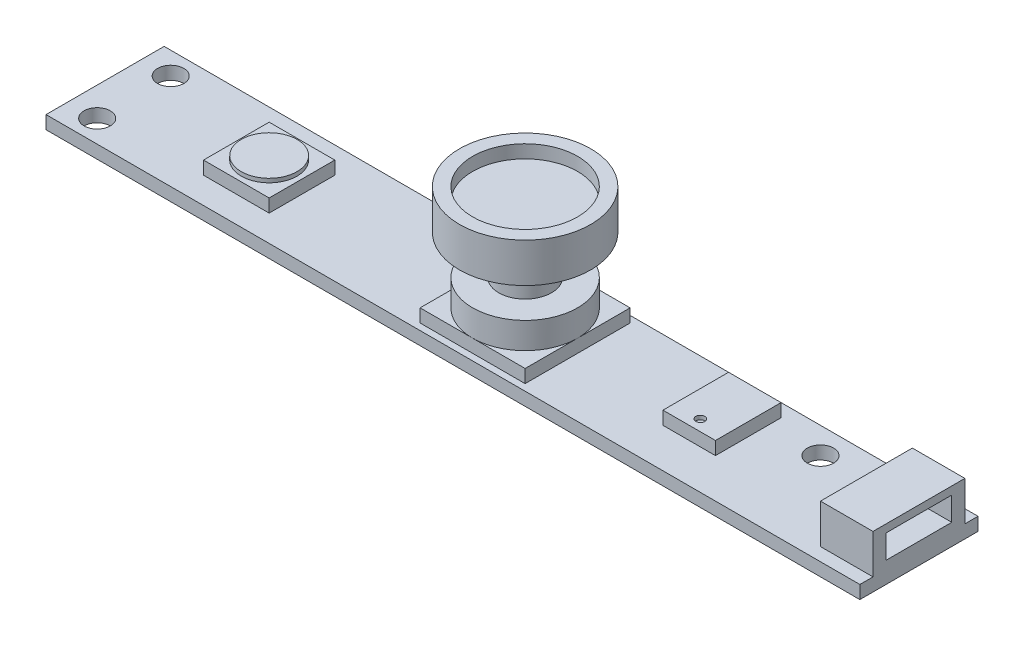
SolidWorks part; units mm, degrees
ref_plane "Front Plane" through (0, 0, 0) normal (0, 0, 1) x (1, 0, 0)
ref_plane "Top Plane" through (0, 0, 0) normal (0, 1, 0) x (1, 0, 0)
ref_plane "Right Plane" through (0, 0, 0) normal (1, 0, 0) x (0, 0, -1)
sketch "Sketch1" plane through (0, 0, 0) normal (0, 1, 0) x (1, 0, 0)
  line L1 (0, 0) -> (62, 0)
  line L2 (0, 0) -> (0, 9)
  line L3 (0, 9) -> (62, 9)
  line L4 (62, 0) -> (62, 9)
  dimension "D1" = 9
  dimension "D2" = 62
extrude "Boss-Extrude1" add sketch "Sketch1" along normal blind 1
sketch "Sketch2" plane through (0, 1, 0) normal (0, 1, 0) x (1, 0, 0)
  line L0 (62, 4.5) -> (0, 4.5) construction
  line L1 (62, 0) -> (62, 9) construction
  line L2 (0, 9) -> (0, 0) construction
  line L3 (31, 9) -> (31, 0) construction
  line L4 (62, 9) -> (0, 9) construction
  line L5 (0, 0) -> (62, 0) construction
  line L6 (62, 4.5) -> (62, 8)
  line L7 (62, 4.5) -> (62, 1)
  line L8 (62, 8) -> (58, 8)
  line L9 (58, 8) -> (58, 1)
  line L10 (58, 1) -> (62, 1)
  dimension "D1" = 3.5
  dimension "D2" = 3.5
  dimension "D3" = 4
extrude "Boss-Extrude2" add sketch "Sketch2" along normal blind 3
sketch "Sketch3" plane through (62, 0, 0) normal (1, 0, 0) x (0, 0, -1)
  line L11 (2, 3.4) -> (7, 3.4)
  line L12 (2, 3.4) -> (2, 1.6)
  line L13 (2, 1.6) -> (7, 1.6)
  line L14 (7, 3.4) -> (7, 1.6)
extrude "Cut-Extrude1" cut sketch "Sketch3" against normal blind 3
sketch "Sketch4" plane through (0, 1, 0) normal (0, 1, 0) x (1, 0, 0)
  line L0 (0, 4.5) -> (62, 4.5) construction
  line L1 (0, 9) -> (0, 0) construction
  line L2 (62, 1) -> (62, 8) construction
  line L4 (62, 9) -> (0, 9) construction
  line L5 (2.2, 9) -> (2.2, 0) construction
  line L6 (0, 0) -> (62, 0) construction
  circle A0 centre (2.2, 7.3) radius 1
  circle A1 centre (2.2, 1.7) radius 1
  circle A2 centre (52, 7) radius 1
extrude "Cut-Extrude2" cut sketch "Sketch4" against normal through all
sketch "Sketch5" plane through (0, 1, 0) normal (0, 1, 0) x (1, 0, 0)
  line L0 (62, 9) -> (62, 8)
  line L1 (62, 1) -> (62, 8) construction
  line L2 (62, 8) -> (31.4894, 8) construction
  line L3 (62, 9) -> (48, 9)
  line L4 (62, 9) -> (0, 9) construction
  line L5 (48, 9) -> (48, 0) construction
  line L6 (0, 0) -> (62, 0) construction
  line L8 (44, 9) -> (44, 0) construction
  line L9 (48, 8) -> (44, 8)
  line L10 (62, 3) -> (38.3098, 3) construction
  line L11 (48, 8) -> (48, 3)
  line L12 (48, 3) -> (44, 3)
  line L13 (44, 8) -> (44, 3)
  dimension "D1" = 1
  dimension "D2" = 14
extrude "Boss-Extrude4" add sketch "Sketch5" along normal blind 1 contours L9 L13 L12 L11
sketch "Sketch6" plane through (0, 1, 0) normal (0, 1, 0) x (1, 0, 0)
  line L0 (0, 9) -> (10, 9)
  line L1 (62, 9) -> (0, 9) construction
  line L2 (10, 9) -> (10, 0) construction
  line L3 (0, 0) -> (62, 0) construction
  line L4 (0, 4.5) -> (24.0117, 4.5) construction
  line L5 (0, 9) -> (0, 0) construction
  line L6 (10, 4.5) -> (10, 7)
  line L7 (10, 7) -> (15, 7)
  line L8 (15, 7) -> (15, 4.5)
  line L9 (15, 4.5) -> (15, 2)
  line L10 (15, 2) -> (10, 2)
  line L11 (10, 2) -> (10, 4.5)
  dimension "D1" = 10
  dimension "D2" = 2.5
  dimension "D3" = 2.5
  dimension "D4" = 5
extrude "Boss-Extrude5" add sketch "Sketch6" along normal blind 1 contours L11 L10 L9 L8 L7 L6
sketch "Sketch7" plane through (0, 2, 0) normal (0, 1, 0) x (1, 0, 0)
  line L0 (12.5, 7) -> (12.5, 2) construction
  line L1 (10, 7) -> (15, 7) construction
  line L2 (15, 2) -> (10, 2) construction
  line L3 (10, 4.5) -> (15, 4.5) construction
  line L4 (10, 2) -> (10, 7) construction
  line L5 (15, 7) -> (15, 2) construction
  circle A0 centre (12.5, 4.5) radius 2.126
extrude "Boss-Extrude6" add sketch "Sketch7" along normal blind 0.3
sketch "Sketch8" plane through (0, 1, 0) normal (0, 1, 0) x (1, 0, 0)
  line L0 (0, 4.5) -> (62, 4.5) construction
  line L1 (0, 9) -> (0, 0) construction
  line L2 (62, 1) -> (62, 8) construction
  line L3 (62, 9) -> (36, 9)
  line L4 (62, 9) -> (0, 9) construction
  line L5 (36, 9) -> (36, 0) construction
  line L6 (0, 0) -> (62, 0) construction
  line L7 (36, 9) -> (28, 9)
  line L8 (28, 9) -> (28, 0) construction
  line L9 (28, 4.5) -> (28, 0.5)
  line L10 (28, 0.5) -> (36, 0.5)
  line L11 (36, 0.5) -> (36, 4.5)
  line L12 (36, 4.5) -> (36, 8.5)
  line L13 (36, 8.5) -> (28, 8.5)
  line L14 (28, 8.5) -> (28, 4.5)
  dimension "D1" = 26
  dimension "D2" = 8
  dimension "D3" = 4
  dimension "D4" = 4
extrude "Boss-Extrude7" add sketch "Sketch8" along normal blind 1 contours L13 L14 L9 L10 L11 L12
sketch "Sketch9" plane through (0, 2, 0) normal (0, 1, 0) x (1, 0, 0)
  line L0 (28, 4.5) -> (36, 4.5) construction
  line L1 (28, 8.5) -> (28, 0.5) construction
  line L2 (36, 0.5) -> (36, 8.5) construction
  line L3 (32, 8.5) -> (32, 0.5) construction
  line L4 (36, 8.5) -> (28, 8.5) construction
  line L5 (28, 0.5) -> (36, 0.5) construction
  circle A0 centre (32, 4.5) radius 4
extrude "Boss-Extrude8" add sketch "Sketch9" along normal blind 2
sketch "Sketch10" plane through (0, 4, 0) normal (0, 1, 0) x (1, 0, 0)
  line L0 (32, 8.5) -> (32, 0.5) construction
  line L1 (28, 4.5) -> (36, 4.5) construction
  circle A0 centre (32, 4.5) radius 4 construction
  circle A1 centre (32, 4.5) radius 2.0145
extrude "Boss-Extrude9" add sketch "Sketch10" along normal blind 3
sketch "Sketch11" plane through (0, 7, 0) normal (0, 1, 0) x (1, 0, 0)
  line L0 (29.9855, 4.5) -> (34.0145, 4.5) construction
  line L1 (32, 6.5145) -> (32, 2.4855) construction
  circle A0 centre (32, 4.5) radius 2.0145 construction
  circle A1 centre (32, 4.5) radius 2.0145 construction
  circle A2 centre (32, 4.5) radius 5
extrude "Boss-Extrude10" add sketch "Sketch11" along normal blind 3
sketch "Sketch12" plane through (0, 10, 0) normal (0, 1, 0) x (1, 0, 0)
  line L0 (32, 9.5) -> (32, -0.5) construction
  circle A0 centre (32, 4.5) radius 5 construction
  circle A1 centre (32, 4.5) radius 4
extrude "Cut-Extrude3" cut sketch "Sketch12" against normal blind 1
sketch "Sketch13" plane through (0, 2, 0) normal (0, 1, 0) x (1, 0, 0)
  line L0 (46, 8) -> (46, 3) construction
  line L1 (48, 8) -> (44, 8) construction
  line L2 (48, 3) -> (44, 3) construction
  circle A0 centre (46, 3.8455) radius 0.3411
extrude "Cut-Extrude4" cut sketch "Sketch13" against normal blind 0.3
